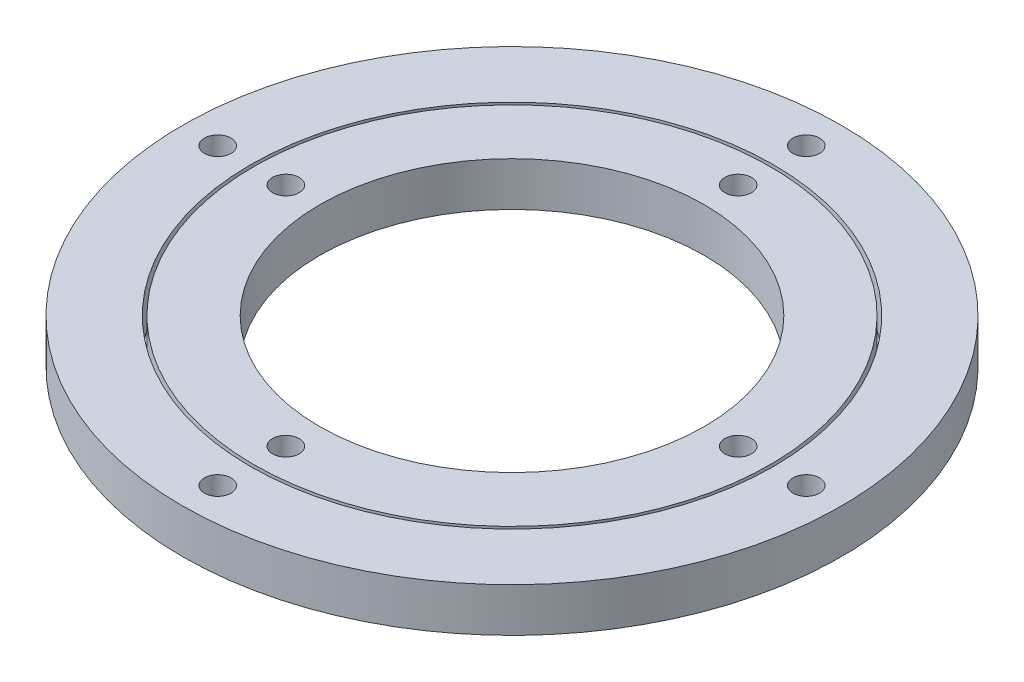
SolidWorks part; units mm, degrees
material "2024 合金"
ref_plane "前视基准面" through (0, 0, 0) normal (0, 0, 1) x (1, 0, 0)
ref_plane "上视基准面" through (0, 0, 0) normal (0, 1, 0) x (1, 0, 0)
ref_plane "右视基准面" through (0, 0, 0) normal (1, 0, 0) x (0, 0, -1)
other "Configuration Table"
sketch "草图1" plane through (0, 0, 0) normal (0, 1, 0) x (1, 0, 0)
  circle A0 centre (0, 0) radius 35
  circle A1 centre (0, 0) radius 60
  dimension "D1" = 70
  dimension "D2" = 120
extrude "凸台-拉伸1" add sketch "草图1" along normal blind 8
sketch "草图2" plane through (0, 8, 0) normal (0, 1, 0) x (1, 0, 0)
  circle A0 centre (0, 0) radius 35 construction
  circle A1 centre (0, 0) radius 60
  circle A2 centre (0, 0) radius 60
  circle A3 centre (0, 0) radius 35
  circle A4 centre (0, 0) radius 47
  circle A5 centre (0, 0) radius 47.6
  dimension "D2" = 0.6
  dimension "D3" = 12
  dimension "D1" = 0
extrude "切除-拉伸1" cut sketch "草图2" against normal offset from surface (7.5 mm away) 0.5 contours A5 A4 up to face at (0, 0, 60)
sketch "草图3" plane through (0, 8, 0) normal (0, 1, 0) x (1, 0, 0)
  line L0 (-38.75, 0) -> (38.75, 0)
  line L1 (-68.4607, 0) -> (68.4607, 0) construction
  circle A0 centre (-41.175, 0) radius 2.425
  circle A1 centre (0, 0) radius 47
  circle A2 centre (0, 0) radius 47
  circle A3 centre (0, 41.175) radius 2.425
  circle A4 centre (41.175, 0) radius 2.425
  circle A5 centre (0, -41.175) radius 2.425
  point P6 (0, 0)
  point P9 (0, 0)
  point P11 (0, 0)
  point P20 (0, 0)
  dimension "D3" = 4.85
  dimension "D2" = 77.5
  dimension "D1" = 0
  dimension "D4" = 4
extrude "切除-拉伸2" cut sketch "草图3" against normal through all contours L1 A0 | A0 L1 | A3 | L1 A4 | A4 L1 | A5
sketch "草图4" plane through (0, 8, 0) normal (0, 1, 0) x (1, 0, 0)
  line L0 (-47.6, 0) -> (-60, 0)
  line L1 (-60, 0) -> (-56, 0)
  circle A0 centre (0, 0) radius 47.6 construction
  circle A1 centre (0, 0) radius 60
  circle A2 centre (0, 0) radius 60
  circle A3 centre (0, 0) radius 47.6
  circle A4 centre (-53.575, 0) radius 2.425
  circle A6 centre (0, 53.575) radius 2.425
  circle A7 centre (53.575, 0) radius 2.425
  circle A8 centre (0, -53.575) radius 2.425
  point P20 (0, 0)
  dimension "D3" = 4.85
  dimension "D2" = 4
  dimension "D1" = 0
  dimension "D4" = 4
extrude "切除-拉伸3" cut sketch "草图4" against normal through all contours A6 | A7 | A8 | L0 A4 | L0 A4
